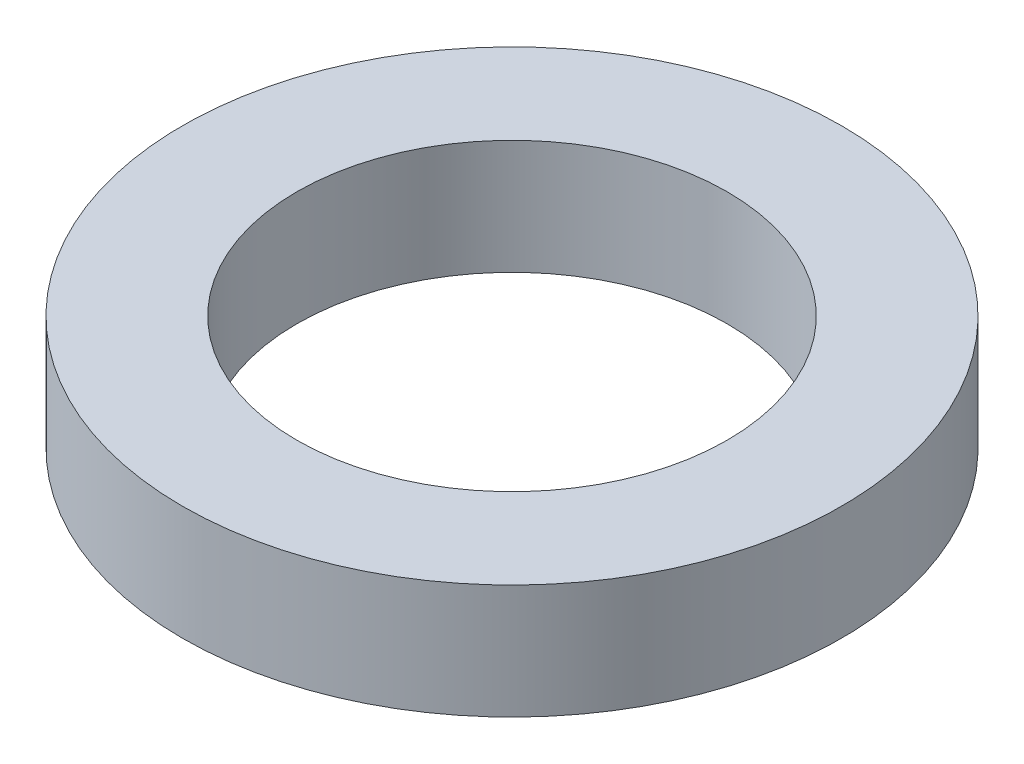
SolidWorks part; units mm, degrees
material "Copper"
ref_plane "Front Plane" through (0, 0, 0) normal (0, 0, 1) x (1, 0, 0)
ref_plane "Top Plane" through (0, 0, 0) normal (0, 1, 0) x (1, 0, 0)
ref_plane "Right Plane" through (0, 0, 0) normal (1, 0, 0) x (0, 0, -1)
sketch "Sketch1" plane through (0, 0, 0) normal (0, 1, 0) x (1, 0, 0)
  circle A0 centre (0, 0) radius 29.21
  circle A1 centre (0, 0) radius 44.734
  dimension "D1" = 58.42
  dimension "D2" = 89.468
extrude "Extrude1" add sketch "Sketch1" along normal blind 15.524
